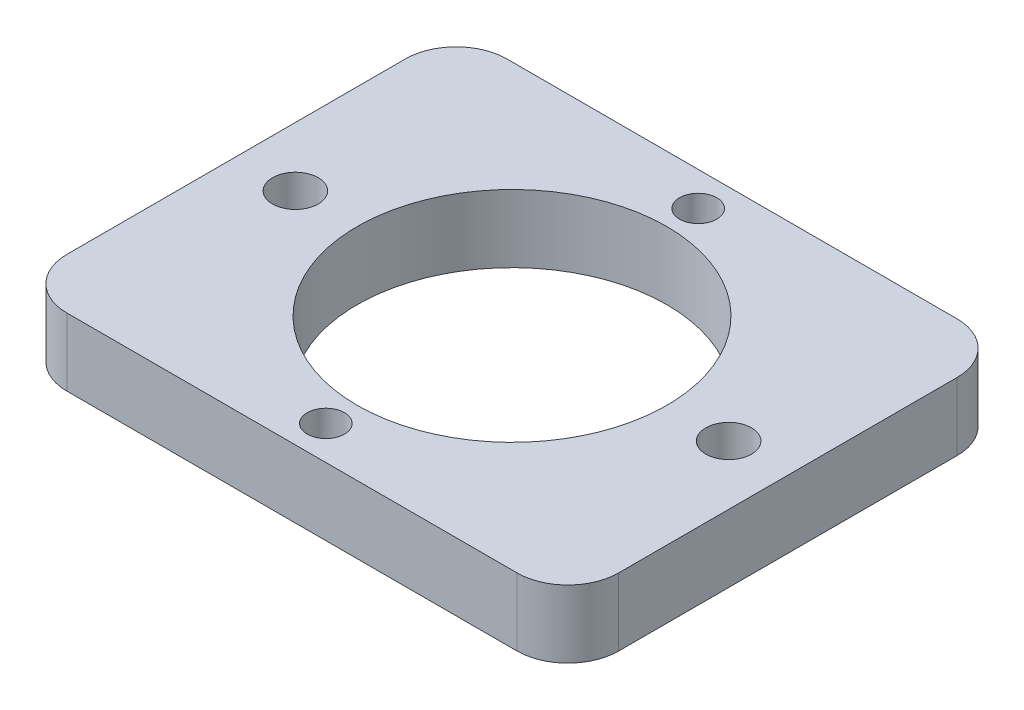
SolidWorks part; units mm, degrees
ref_plane "Front" through (0, 0, 0) normal (0, 0, 1) x (1, 0, 0)
ref_plane "Top" through (0, 0, 0) normal (0, 1, 0) x (1, 0, 0)
ref_plane "Right" through (0, 0, 0) normal (1, 0, 0) x (0, 0, -1)
sketch "Sketch1" plane through (0, 0, 0) normal (0, 1, 0) x (1, 0, 0)
  line L1 (0, 0) -> (32.6, 0)
  line L2 (0, 0) -> (0, -26)
  line L3 (0, -26) -> (32.6, -26)
  line L4 (32.6, 0) -> (32.6, -26)
  dimension "D1" = 26
  dimension "D2" = 32.6
extrude "Boss-Extrude1" add sketch "Sketch1" along normal blind 4
sketch "Sketch2" plane through (0, 4, 0) normal (0, 1, 0) x (1, 0, 0)
  line L0 (0, 0) -> (0, -26) construction
  line L1 (32.6, -26) -> (32.6, 0) construction
  line L2 (32.6, 0) -> (0, 0) construction
  line L3 (0, -26) -> (32.6, -26) construction
  circle A0 centre (16.3, -13) radius 9.15
  circle A1 centre (3.5, -13) radius 1.35
  circle A2 centre (29.1, -13) radius 1.35
  circle A3 centre (16.3, -2) radius 1.1
  circle A4 centre (16.3, -24) radius 1.1
  dimension "D1" = 18.3
  dimension "D2" = 2.7
  dimension "D3" = 2.7
  dimension "D4" = 2.2
  dimension "D5" = 2.2
  dimension "D6" = 3.5
  dimension "D7" = 3.5
  dimension "D8" = 2
  dimension "D9" = 2
extrude "Cut-Extrude1" cut sketch "Sketch2" against normal blind 4
fillet "Fillet1" radius 3 4 edges at (32.6, 2, 26) (0, 2, 26) (32.6, 2, 0) (0, 2, 0)
